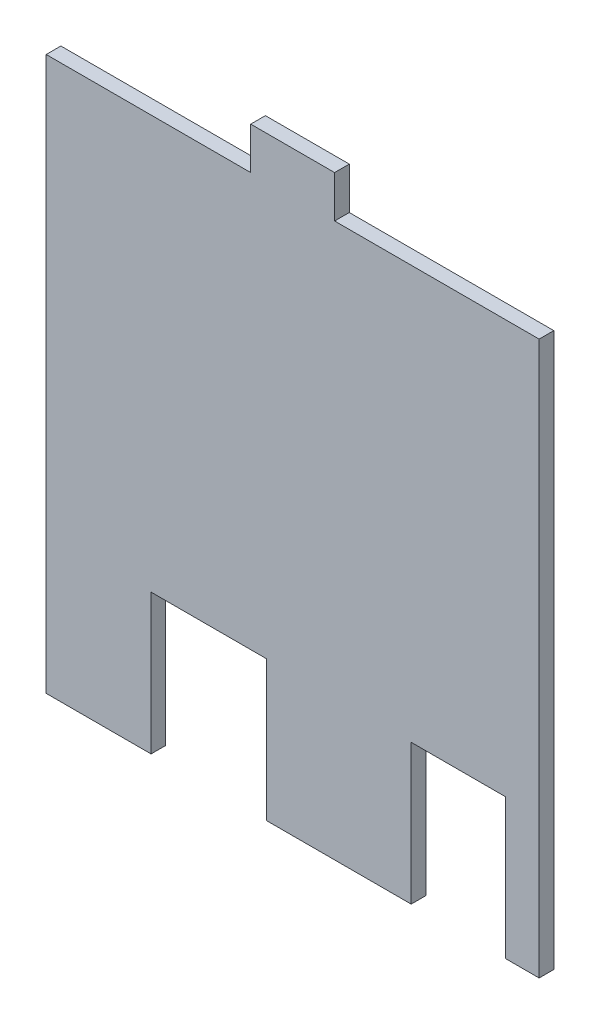
SolidWorks part; units mm, degrees
ref_plane "Front Plane" through (0, 0, 0) normal (0, 0, 1) x (1, 0, 0)
ref_plane "Top Plane" through (0, 0, 0) normal (0, 1, 0) x (1, 0, 0)
ref_plane "Right Plane" through (0, 0, 0) normal (1, 0, 0) x (0, 0, -1)
sketch "Sketch1" plane through (0, 0, 0) normal (0, 0, 1) x (1, 0, 0)
  line L0 (5.08, 33.5) -> (29.845, 33.5)
  line L1 (-29.845, -33.5) -> (-17.145, -33.5)
  line L2 (-29.845, -33.5) -> (-29.845, 33.5)
  line L3 (-29.845, 33.5) -> (-5.08, 33.5)
  line L4 (29.845, -33.5) -> (29.845, 33.5)
  line L5 (-29.845, -33.5) -> (29.845, 33.5) construction
  line L6 (-29.845, 33.5) -> (29.845, -33.5) construction
  line L8 (-5.08, 33.5) -> (-5.08, 38.58)
  line L9 (-5.08, 38.58) -> (5.08, 38.58)
  line L10 (5.08, 33.5) -> (5.08, 38.58)
  line L11 (-3.175, -33.5) -> (14.351, -33.5)
  line L12 (-17.145, -16.53) -> (-3.175, -16.53)
  line L13 (-17.145, -16.53) -> (-17.145, -33.5)
  line L15 (-3.175, -16.53) -> (-3.175, -33.5)
  line L16 (14.351, -16.53) -> (25.781, -16.53)
  line L17 (14.351, -16.53) -> (14.351, -33.5)
  line L19 (25.781, -16.53) -> (25.781, -33.5)
  line L20 (25.781, -33.5) -> (29.845, -33.5)
  point P0 (0, 0)
  dimension "D1" = 59.69
  dimension "D2" = 67
  dimension "D3" = 10.16
  dimension "D4" = 5.08
  dimension "D6" = 13.97
  dimension "D7" = 16.97
  dimension "D8" = 11.43
  dimension "D9" = 4.064
  dimension "D10" = 12.7
extrude "Boss-Extrude1" add sketch "Sketch1" along normal blind 1.778
